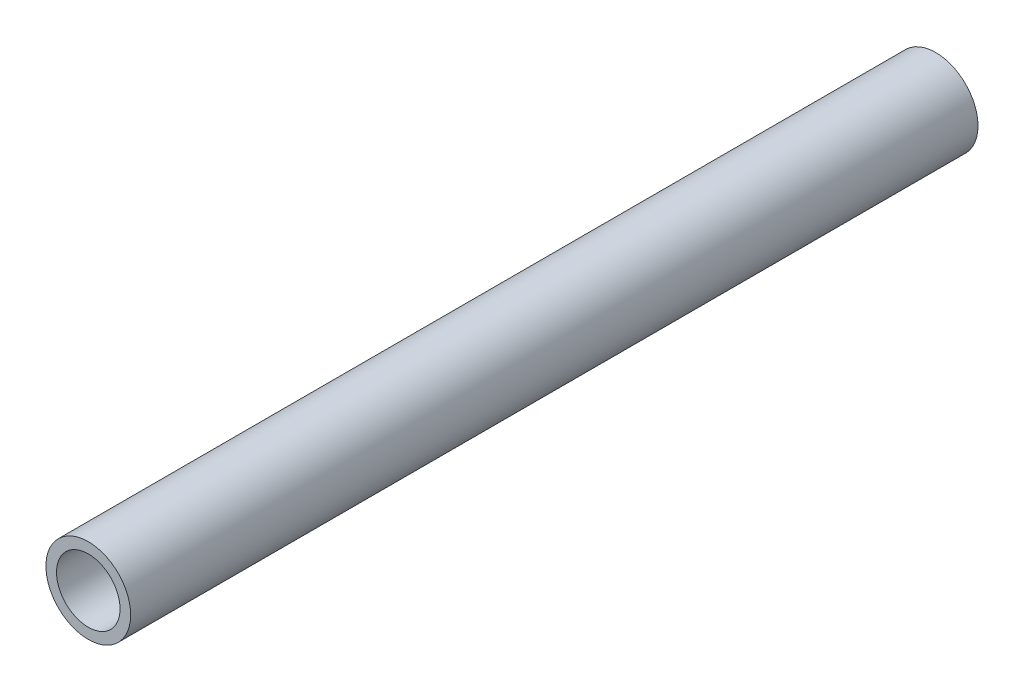
SolidWorks part; units mm, degrees
ref_plane "前视基准面" through (0, 0, 0) normal (0, 0, 1) x (1, 0, 0)
ref_plane "上视基准面" through (0, 0, 0) normal (0, 1, 0) x (1, 0, 0)
ref_plane "右视基准面" through (0, 0, 0) normal (1, 0, 0) x (0, 0, -1)
sketch "草图1" plane through (0, 0, 0) normal (0, 0, 1) x (1, 0, 0)
  circle A0 centre (0, 0) radius 8
  circle A1 centre (0, 0) radius 6
extrude "凸台-拉伸1" add sketch "草图1" along normal blind 160
